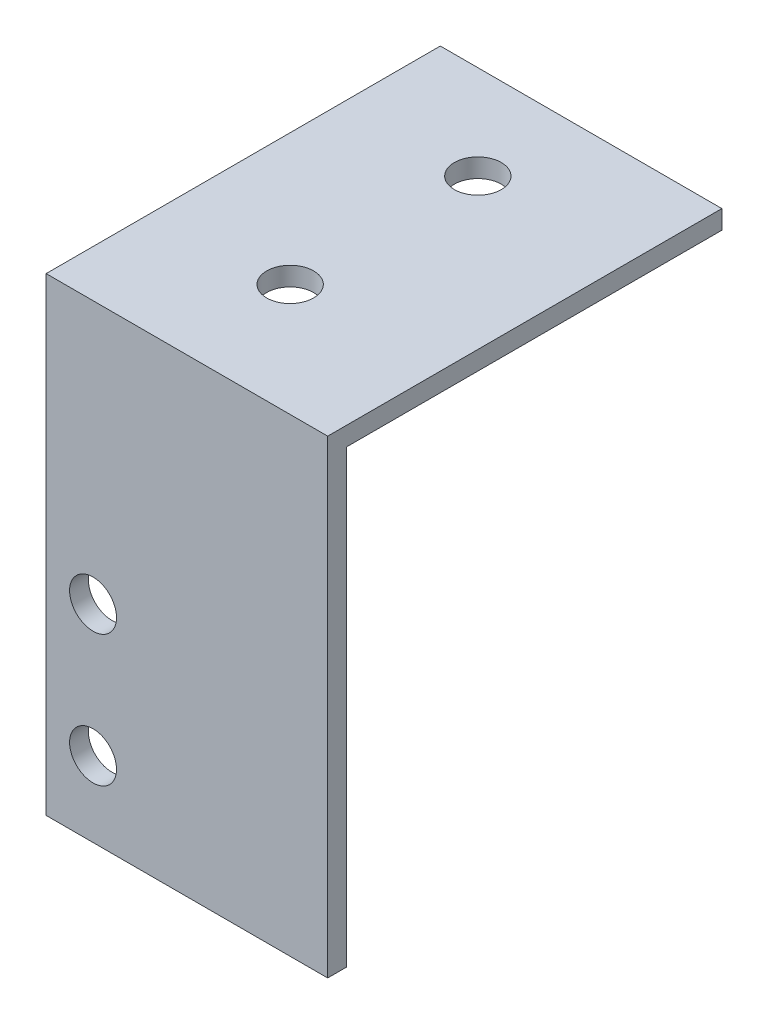
SolidWorks part; units mm, degrees
ref_plane "正面" through (0, 0, 0) normal (0, 0, 1) x (1, 0, 0)
ref_plane "平面" through (0, 0, 0) normal (0, 1, 0) x (1, 0, 0)
ref_plane "右側面" through (0, 0, 0) normal (1, 0, 0) x (0, 0, -1)
sketch "ｽｹｯﾁ1" plane through (0, 0, 0) normal (0, 0, 1) x (1, 0, 0)
  line L1 (0, 0) -> (15, 0)
  line L2 (0, 0) -> (0, 25)
  line L3 (0, 25) -> (15, 25)
  line L4 (15, 0) -> (15, 25)
  dimension "D1" = 25
  dimension "D2" = 15
extrude "ﾎﾞｽ - 押し出し1" add sketch "ｽｹｯﾁ1" along normal blind 1 contours L3 L4 L1 L2
hole_wizard "M3x0.5 ねじ穴1" positions "ｽｹｯﾁ2" profile "ｽｹｯﾁ3" tap size "M3x0.5" standard "JIS"
sketch "ｽｹｯﾁ2" plane through (0, 0, 0) normal (0, 0, -1) x (-1, 0, 0)
  line L0 (0, 0) -> (0, 25) construction
  line L1 (0, 0) -> (-15, 0) construction
  point P0 (-2.5, 11)
  point P2 (-2.5, 4)
  dimension "D1" = 2.5
  dimension "D2" = 2.5
  dimension "D3" = 4
  dimension "D4" = 7
sketch "ｽｹｯﾁ3" plane through (2.5, 11, 0) normal (1, 0, 0) x (0, 1, 0)
  line L0 (0, 0) -> (0, 9.2511)
  line L1 (0, 9.2511) -> (1.25, 8.5)
  line L2 (1.25, 8.5) -> (1.25, 0)
  line L5 (1.25, 0) -> (0, 0)
  line L10 (0, 9.2511) -> (-1.25, 8.5) construction
  line L11 (0, -6.35) -> (0, 107.95) construction
  dimension "ねじ下穴ﾄﾞﾘﾙ直径" = 2.5
  dimension "ねじ下穴ﾄﾞﾘﾙの深さ" = 8.5
  dimension "ﾄﾞﾘﾙ角度" = 118
sketch "ｽｹｯﾁ4" plane through (0, 0, 0) normal (0, 0, -1) x (-1, 0, 0)
  line L0 (-15, 0) -> (-15, 25) construction
  line L1 (0, 25) -> (-15, 25)
  line L2 (0, 25) -> (0, 24)
  line L3 (0, 24) -> (-15, 24)
  line L4 (-15, 25) -> (-15, 24)
  dimension "D1" = 1
extrude "ﾎﾞｽ - 押し出し2" add sketch "ｽｹｯﾁ4" along normal blind 20
hole_wizard "M3x0.5 ねじ穴2" positions "ｽｹｯﾁ5" profile "ｽｹｯﾁ6" tap size "M3x0.5" standard "JIS"
sketch "ｽｹｯﾁ5" plane through (0, 24, 0) normal (0, -1, 0) x (-1, 0, 0)
  line L0 (0, 20) -> (-15, 20) construction
  line L1 (0, 20) -> (0, 0) construction
  point P0 (-7, 5)
  point P2 (-7, 15)
  point P7 (0, 0)
  point P10 (0, 0)
  dimension "D1" = 5
  dimension "D2" = 10
  dimension "D3" = 7
sketch "ｽｹｯﾁ6" plane through (7, 24, -5) normal (1, 0, 0) x (0, 0, -1)
  line L0 (0, 0) -> (0, 9.2511)
  line L1 (0, 9.2511) -> (1.25, 8.5)
  line L2 (1.25, 8.5) -> (1.25, 0)
  line L5 (1.25, 0) -> (0, 0)
  line L10 (0, 9.2511) -> (-1.25, 8.5) construction
  line L11 (0, -6.35) -> (0, 107.95) construction
  dimension "ねじ下穴ﾄﾞﾘﾙ直径" = 2.5
  dimension "ねじ下穴ﾄﾞﾘﾙの深さ" = 8.5
  dimension "ﾄﾞﾘﾙ角度" = 118
